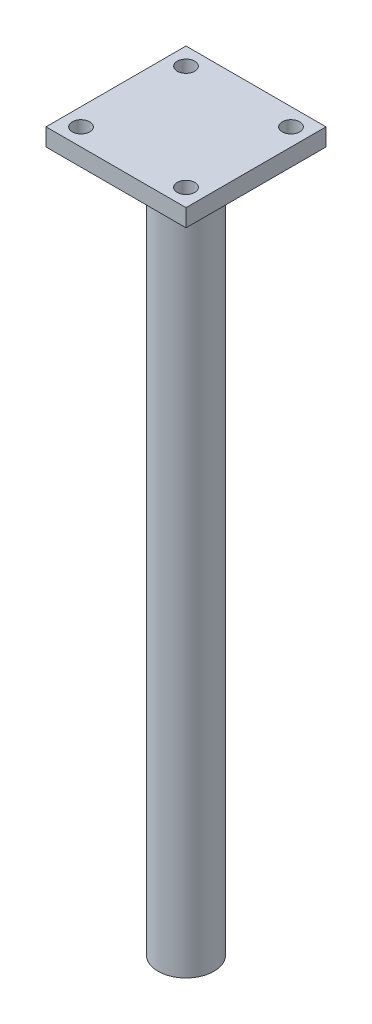
SolidWorks part; units mm, degrees
ref_plane "前视基准面" through (0, 0, 0) normal (0, 0, 1) x (1, 0, 0)
ref_plane "上视基准面" through (0, 0, 0) normal (0, 1, 0) x (1, 0, 0)
ref_plane "右视基准面" through (0, 0, 0) normal (1, 0, 0) x (0, 0, -1)
sketch "草图1" plane through (0, 0, 0) normal (0, 1, 0) x (1, 0, 0)
  circle A0 centre (0, 0) radius 8
  dimension "D1" = 16
extrude "凸台-拉伸1" add sketch "草图1" along normal blind 200
sketch "草图2" plane through (0, 200, 0) normal (0, 1, 0) x (1, 0, 0)
  line L1 (-20, -20) -> (20, -20)
  line L2 (-20, -20) -> (-20, 20)
  line L3 (-20, 20) -> (20, 20)
  line L4 (20, -20) -> (20, 20)
  line L5 (-20, -20) -> (20, 20) construction
  line L6 (-20, 20) -> (20, -20) construction
  point P0 (0, 0)
  dimension "D1" = 40
extrude "凸台-拉伸2" add sketch "草图2" along normal blind 5
sketch "草图3" plane through (0, 205, 0) normal (0, 1, 0) x (1, 0, 0)
  line L1 (-15, -15) -> (15, -15) construction
  line L2 (-15, -15) -> (-15, 15) construction
  line L3 (-15, 15) -> (15, 15) construction
  line L4 (15, -15) -> (15, 15) construction
  line L5 (-15, -15) -> (15, 15) construction
  line L6 (-15, 15) -> (15, -15) construction
  circle A0 centre (-15, 15) radius 2.5
  circle A1 centre (15, 15) radius 2.5
  circle A2 centre (15, -15) radius 2.5
  circle A3 centre (-15, -15) radius 2.5
  point P0 (0, 0)
  dimension "D2" = 5
  dimension "D1" = 30
extrude "切除-拉伸1" cut sketch "草图3" against normal blind 5
